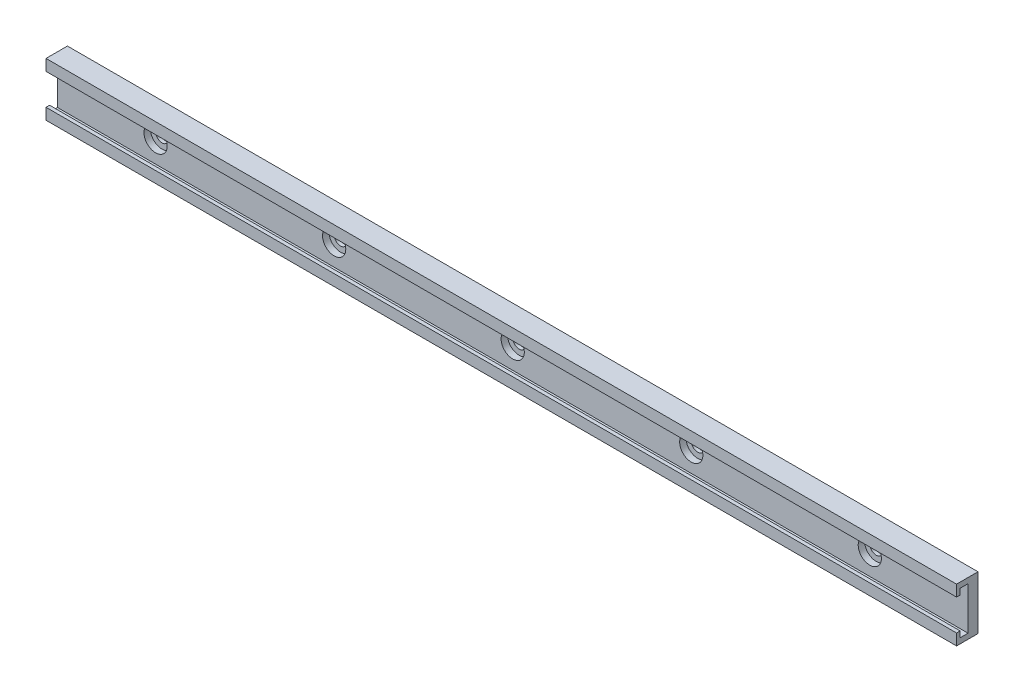
SolidWorks part; units mm, degrees
material "6061 合金"
ref_plane "前视基准面" through (0, 0, 0) normal (0, 0, 1) x (1, 0, 0)
ref_plane "上视基准面" through (0, 0, 0) normal (0, 1, 0) x (1, 0, 0)
ref_plane "右视基准面" through (0, 0, 0) normal (1, 0, 0) x (0, 0, -1)
sketch "草图1" plane through (0, 0, 0) normal (1, 0, 0) x (0, 0, -1)
  line L0 (-5, 4.35) -> (-6, 4.35)
  line L1 (-6, 4.35) -> (-6, 7.5)
  line L2 (-6, 7.5) -> (0, 7.5)
  line L3 (0, 7.5) -> (0, -7.5)
  line L4 (-5, 4.35) -> (-5, 6)
  line L5 (-5, 6) -> (-2.8, 6)
  line L6 (-2.8, 6) -> (-2.8, -6)
  line L7 (55, 0) -> (-55, 0) construction
  line L8 (-5, -6) -> (-2.8, -6)
  line L9 (-5, -4.35) -> (-5, -6)
  line L10 (-6, -7.5) -> (0, -7.5)
  line L11 (-6, -4.35) -> (-6, -7.5)
  line L12 (-5, -4.35) -> (-6, -4.35)
  line L13 (-7, 3.9) -> (-7, -3.9)
  line L14 (-7, 3.9) -> (-4.9, 3.9)
  line L15 (-4.9, 3.9) -> (-4.9, 5.9)
  line L16 (-4.9, 5.9) -> (-2.9, 5.9)
  line L17 (-2.9, 5.9) -> (-2.9, 3.2)
  line L18 (-2.9, 3.2) -> (-3.5, 1.95)
  line L19 (-3.5, 1.95) -> (-3.5, -1.95)
  line L20 (-2.9, -3.2) -> (-3.5, -1.95)
  line L21 (-2.9, -5.9) -> (-2.9, -3.2)
  line L22 (-4.9, -5.9) -> (-2.9, -5.9)
  line L23 (-4.9, -3.9) -> (-4.9, -5.9)
  line L24 (-7, -3.9) -> (-4.9, -3.9)
  line L25 (-317.1337, 1113.4359) -> (-53.8004, 1113.4359) construction
  line L26 (23.8654, 1077.0309) -> (287.1987, 1077.0309) construction
  point P19 (-4.6783, -2.0661)
  point P21 (-3.3875, 3.2834)
  point P24 (-5.1252, 3.9)
  point P30 (-7, -3.7653)
  point P31 (-5.2967, 5.8084)
  point P34 (-4.8878, -3.9)
  point P37 (-3.5, -2.1351)
  point P38 (-3.5, -1.95)
  point P39 (-3.5, -1.95)
  point P40 (-3.5, 1.95)
  point P41 (-2.9, 3.5256)
  dimension "D1" = 15
  dimension "D2" = 6
  dimension "D3" = 2.8
  dimension "D4" = 8.7
  dimension "D5" = 7
  dimension "D6" = 7.8
  dimension "D7" = 3.5
  dimension "D8" = 4.1
  dimension "D9" = 11.8
  dimension "D10" = 0.1
  dimension "D11" = 1
  dimension "D13" = 3.9
  dimension "D14" = 2.7
  dimension "D15" = 0.1
extrude "凸台-拉伸1" add sketch "草图1" along normal mid plane 255 contours L9 L12 L11 L10 L3 L2 L1 L0 L4 L5 L6 L8
hole_wizard "孔1" positions "草图2" profile "草图3" legacy end condition through all
sketch "草图2" plane through (0, 0, 2.8) normal (0, 0, 1) x (1, 0, 0)
  line L0 (-100, 0) -> (-50, 0) construction
  point P0 (-100, 0)
  point P22 (-50, 0)
  point P23 (0, 0)
  point P24 (50, 0)
  point P25 (100, 0)
  point P27 (-65.1378, 0)
  point P28 (0, 0)
  dimension "D1" = 5
  dimension "D2" = 50
sketch "草图3" plane through (-100, 0, 2.8) normal (1, 0, 0) x (0, -1, 0)
  line L0 (0, 0) -> (0, 2.8)
  line L1 (0, 2.8) -> (1.75, 2.8)
  line L2 (1.75, 2.8) -> (1.75, 1.8)
  line L3 (1.75, 1.8) -> (3.25, 1.8)
  line L4 (3.25, 1.8) -> (3.25, 0)
  line L5 (3.25, 0) -> (0, 0)
  line L6 (0, 110) -> (0, -10) construction
  dimension "直径" = 3.5
  dimension "深度" = 2.8
  dimension "柱坑直径" = 6.5
  dimension "柱坑深度" = 1.8
